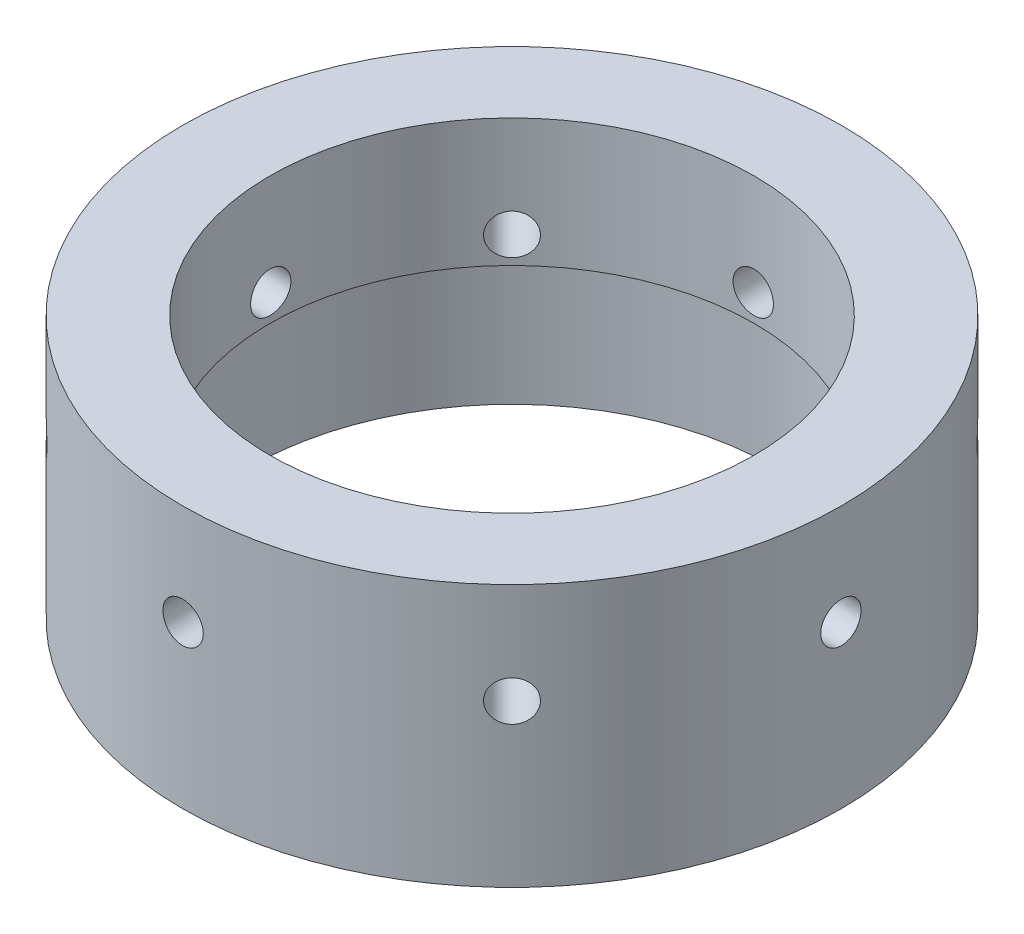
SolidWorks part; units mm, degrees
ref_plane "Alzado" through (0, 0, 0) normal (0, 0, 1) x (1, 0, 0)
ref_plane "Planta" through (0, 0, 0) normal (0, 1, 0) x (1, 0, 0)
ref_plane "Vista lateral" through (0, 0, 0) normal (1, 0, 0) x (0, 0, -1)
sketch "Croquis1" plane through (0, 0, 0) normal (1, 0, 0) x (0, 0, -1)
  line L0 (0, 0) -> (0, 62.948) construction
  line L1 (-49, 53) -> (-36, 53)
  line L2 (-36, 53) -> (-36, 34)
  line L4 (-39, 34) -> (-39, 14)
  line L6 (-49, 14) -> (-49, 53)
  line L7 (-39, 34) -> (-36, 34)
  line L8 (-39, 14) -> (-49, 14)
  dimension "D1" = 36
  dimension "D2" = 13
  dimension "D3" = 10
  dimension "D7" = 19
revolve "Revolución1" add sketch "Croquis1" angle 360 about L0
sketch "Croquis2" plane through (0, 0, 0) normal (1, 0, 0) x (0, 0, -1)
  line L0 (0, 53) -> (0, 38) construction
  line L1 (36, 53) -> (-36, 53) construction
  circle A0 centre (0, 38) radius 3
  dimension "D1" = 6
  dimension "D2" = 15
extrude "Cortar-Extruir1" cut sketch "Croquis2" against normal through all both and the other way through all
sketch "Croquis3" plane through (0, 0, 0) normal (0, 0, 1) x (1, 0, 0)
  line L0 (0, 53) -> (0, 16.2382) construction
  line L1 (49, 53) -> (-49, 53) construction
  circle A0 centre (0, 38) radius 3
  dimension "D1" = 6
  dimension "D2" = 15
extrude "Cortar-Extruir2" cut sketch "Croquis3" against normal through all both and the other way through all
ref_plane "Plano1" through (0, 0, 0) normal (0.7071, 0, -0.7071) x (-0.7071, 0, -0.7071)
sketch "Croquis4" plane through (0, 0, 0) normal (0.7071, 0, -0.7071) x (-0.7071, 0, -0.7071)
  line L0 (0, 0) -> (0, 65.1838) construction
  circle A0 centre (0, 38.3621) radius 3
  dimension "D1" = 6
extrude "Cortar-Extruir3" cut sketch "Croquis4" against normal through all both and the other way through all
ref_plane "Plano2" through (0, 0, 0) normal (0.7071, 0, 0.7071) x (0.7071, 0, -0.7071)
sketch "Croquis5" plane through (0, 0, 0) normal (0.7071, 0, 0.7071) x (0.7071, 0, -0.7071)
  line L0 (49, 53) -> (-49, 53) construction
  circle A0 centre (0, 38) radius 3
  dimension "D2" = 6
  dimension "D1" = 15
extrude "Cortar-Extruir4" cut sketch "Croquis5" against normal through all both and the other way through all
